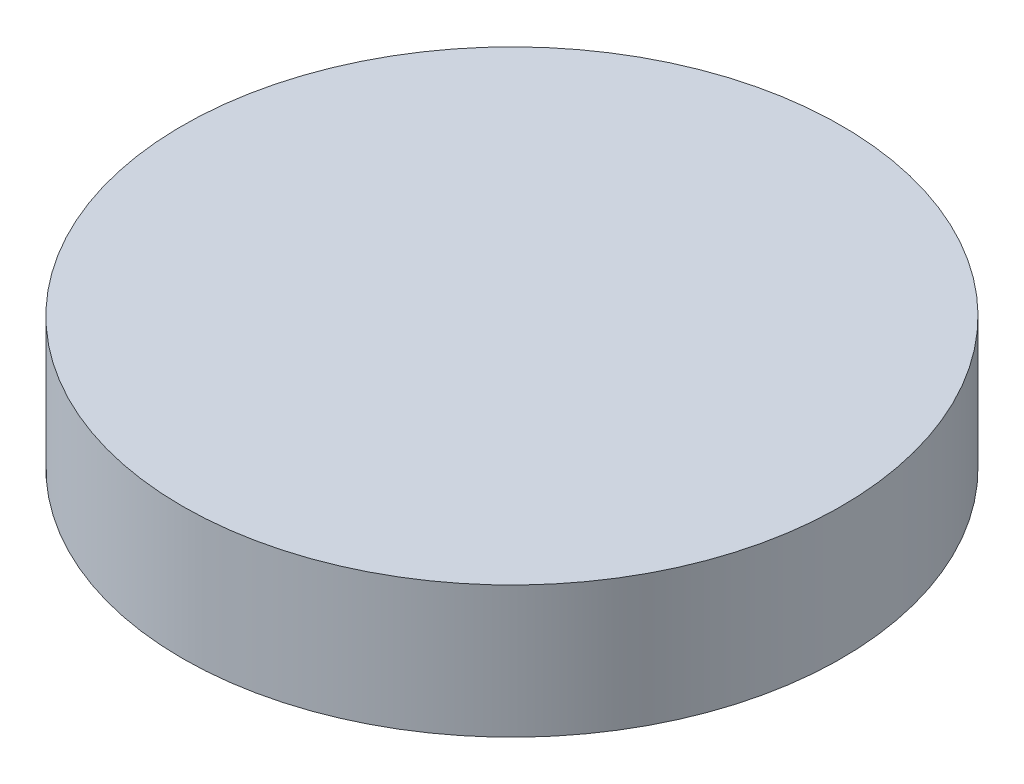
SolidWorks part; units mm, degrees
ref_plane "Front Plane" through (0, 0, 0) normal (0, 0, 1) x (1, 0, 0)
ref_plane "Top Plane" through (0, 0, 0) normal (0, 1, 0) x (1, 0, 0)
ref_plane "Right Plane" through (0, 0, 0) normal (1, 0, 0) x (0, 0, -1)
sketch "Sketch1" plane through (0, 0, 0) normal (0, 1, 0) x (1, 0, 0)
  circle A0 centre (0, 0) radius 6.35
  dimension "D1" = 12.7
extrude "Boss-Extrude1" add sketch "Sketch1" along normal blind 2.54
